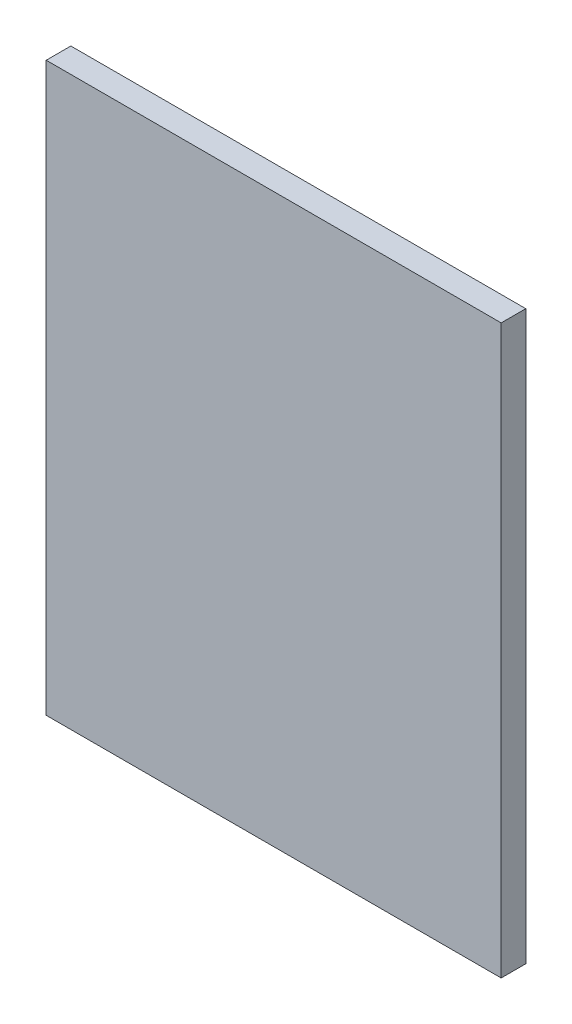
SolidWorks part; units mm, degrees
material "PVC Rígido"
ref_plane "Alzado" through (0, 0, 0) normal (0, 0, 1) x (1, 0, 0)
ref_plane "Planta" through (0, 0, 0) normal (0, 1, 0) x (1, 0, 0)
ref_plane "Vista lateral" through (0, 0, 0) normal (1, 0, 0) x (0, 0, -1)
sketch "Croquis1" plane through (0, 0, 0) normal (0, 0, 1) x (1, 0, 0)
  line L1 (-21.25, -26.5) -> (21.25, -26.5)
  line L2 (-21.25, -26.5) -> (-21.25, 26.5)
  line L3 (-21.25, 26.5) -> (21.25, 26.5)
  line L4 (21.25, -26.5) -> (21.25, 26.5)
  line L5 (-21.25, -26.5) -> (21.25, 26.5) construction
  line L6 (-21.25, 26.5) -> (21.25, -26.5) construction
  point P0 (0, 0)
  dimension "D1" = 53
  dimension "D2" = 42.5
extrude "Saliente-Extruir1" add sketch "Croquis1" along normal blind 2.3
